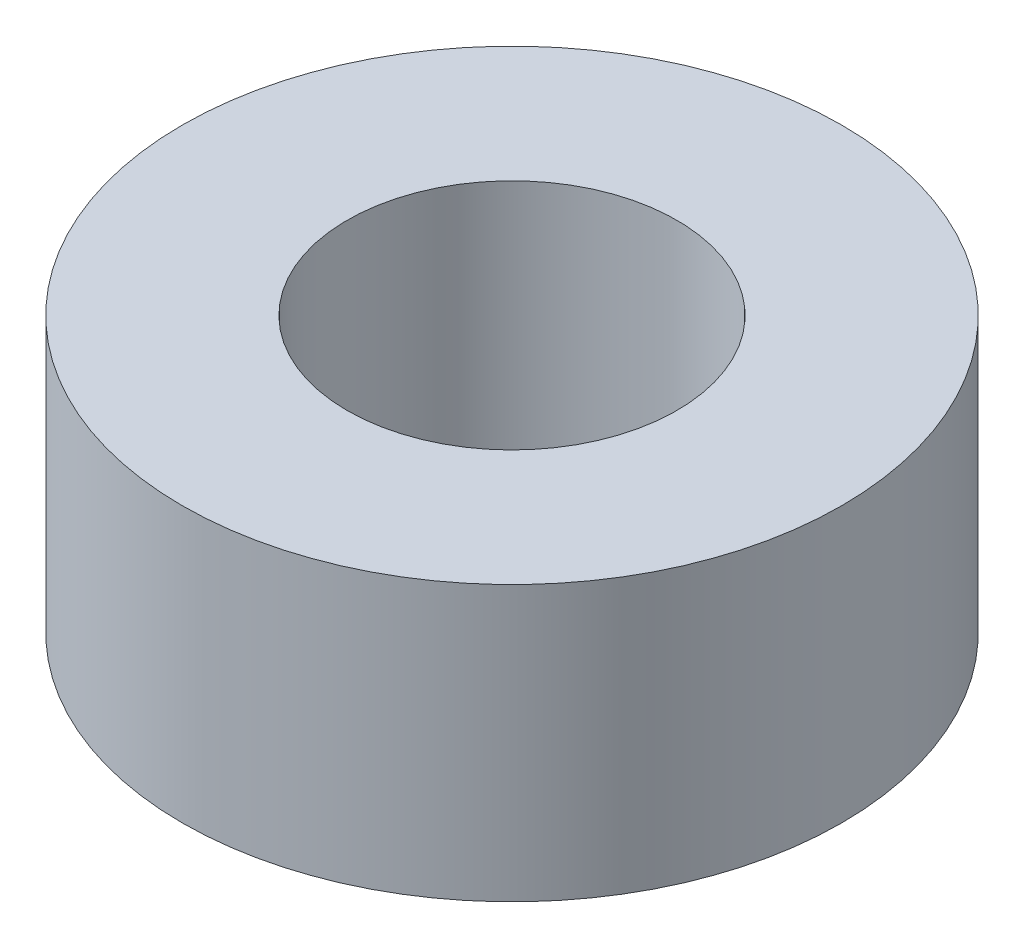
SolidWorks part; units mm, degrees
ref_plane "Plan de face" through (0, 0, 0) normal (0, 0, 1) x (1, 0, 0)
ref_plane "Plan de dessus" through (0, 0, 0) normal (0, 1, 0) x (1, 0, 0)
ref_plane "Plan de droite" through (0, 0, 0) normal (1, 0, 0) x (0, 0, -1)
sketch "Esquisse1" plane through (0, 0, 0) normal (0, 1, 0) x (1, 0, 0)
  circle A0 centre (0, 0) radius 3
  circle A1 centre (0, 0) radius 1.5
  dimension "D1" = 6
  dimension "D2" = 3
extrude "Boss.-Extru.1" add sketch "Esquisse1" along normal blind 2.5
